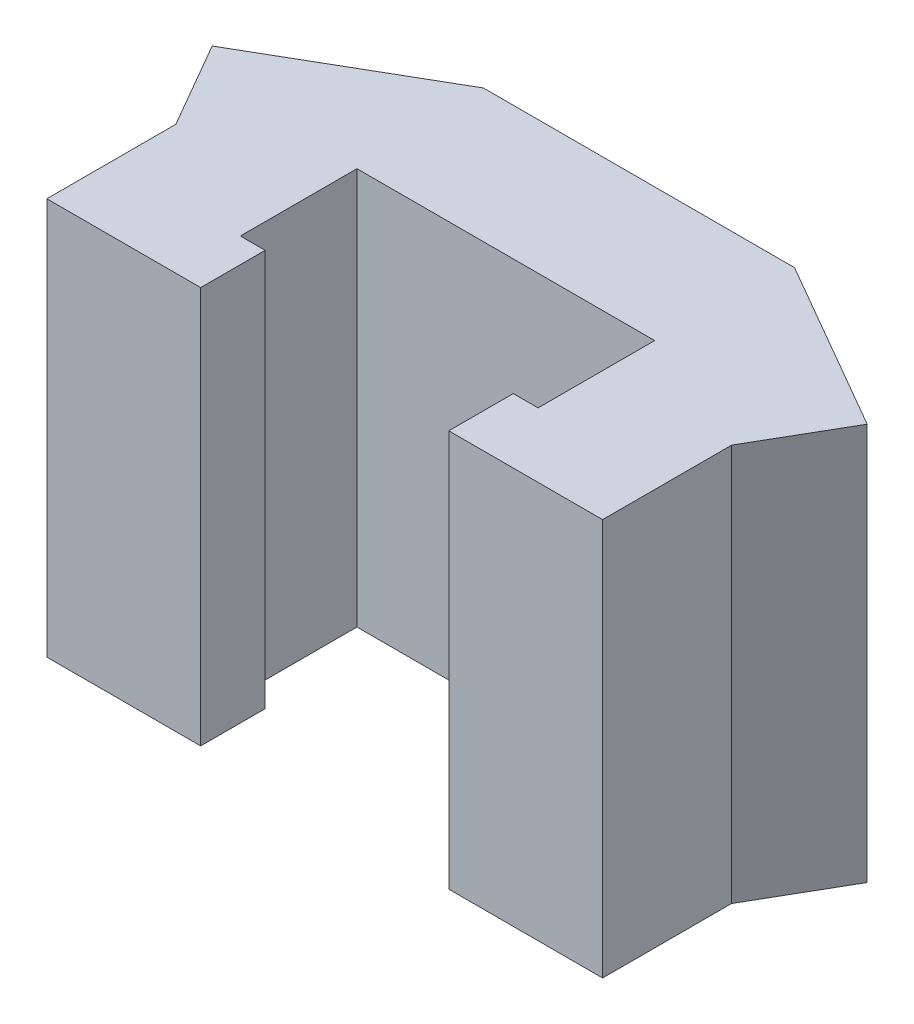
SolidWorks part; units mm, degrees
ref_plane "前基準面" through (0, 0, 0) normal (0, 0, 1) x (1, 0, 0)
ref_plane "上基準面" through (0, 0, 0) normal (0, 1, 0) x (1, 0, 0)
ref_plane "右基準面" through (0, 0, 0) normal (1, 0, 0) x (0, 0, -1)
sketch "草圖2" plane through (0, 0, 0) normal (0, 1, 0) x (1, 0, 0)
  line L0 (-15.0293, -9.2212) -> (-12.5293, -9.2212)
  line L1 (-12.5293, -9.2212) -> (-12.5293, -15.7212)
  line L2 (-12.5293, -15.7212) -> (-28.0293, -15.7212)
  line L3 (-28.0293, -15.7212) -> (-28.0293, -2.7212)
  line L4 (-28.0293, -2.7212) -> (-33.0293, 5.9391)
  line L5 (-33.0293, 5.9391) -> (-15.7088, 15.9391)
  line L6 (-15.7088, 15.9391) -> (15.6502, 15.9391)
  line L7 (-0.0293, 15.9391) -> (-0.0293, -1.1056) construction
  line L8 (14.9707, 2.5288) -> (-15.0293, 2.5288)
  line L9 (-15.0293, 2.5288) -> (-15.0293, -9.2212)
  line L10 (14.9707, 2.5288) -> (14.9707, -9.2212)
  line L11 (32.9707, 5.9391) -> (15.6502, 15.9391)
  line L12 (27.9707, -2.7212) -> (32.9707, 5.9391)
  line L13 (27.9707, -15.7212) -> (27.9707, -2.7212)
  line L14 (12.4707, -15.7212) -> (27.9707, -15.7212)
  line L15 (12.4707, -9.2212) -> (12.4707, -15.7212)
  line L16 (14.9707, -9.2212) -> (12.4707, -9.2212)
  point P13 (-0.0293, 2.5288)
  dimension "D1" = 13
  dimension "D2" = 30
  dimension "D3" = 10
  dimension "D4" = 20
extrude "填料-伸長1" add sketch "草圖2" along normal blind 40
